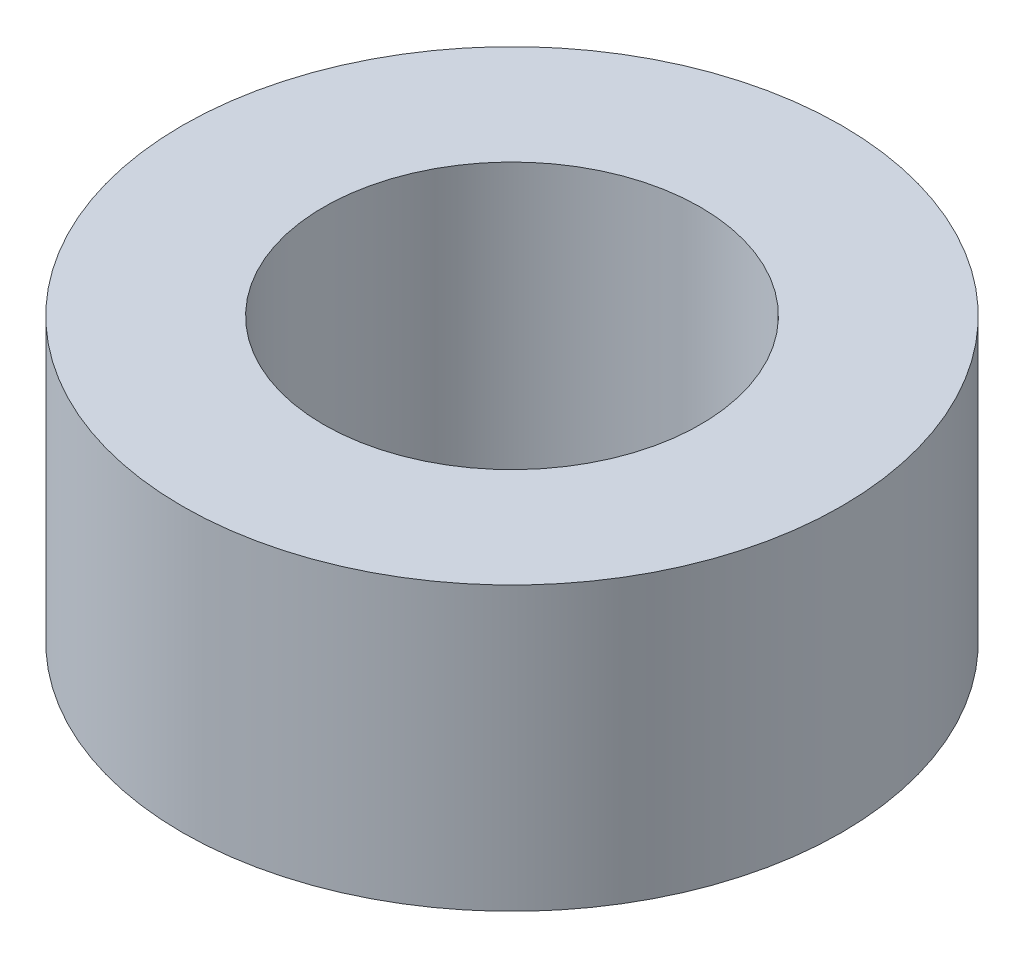
SolidWorks part; units mm, degrees
material "Acrylic (Medium-high impact)"
ref_plane "Front Plane" through (0, 0, 0) normal (0, 0, 1) x (1, 0, 0)
ref_plane "Top Plane" through (0, 0, 0) normal (0, 1, 0) x (1, 0, 0)
ref_plane "Right Plane" through (0, 0, 0) normal (1, 0, 0) x (0, 0, -1)
sketch "Sketch1" plane through (0, 0, 0) normal (0, 1, 0) x (1, 0, 0)
  circle A0 centre (0, 0) radius 3.5
  circle A1 centre (0, 0) radius 2
  dimension "D1" = 4
  dimension "D2" = 7
extrude "Boss-Extrude1" add sketch "Sketch1" along normal blind 3
